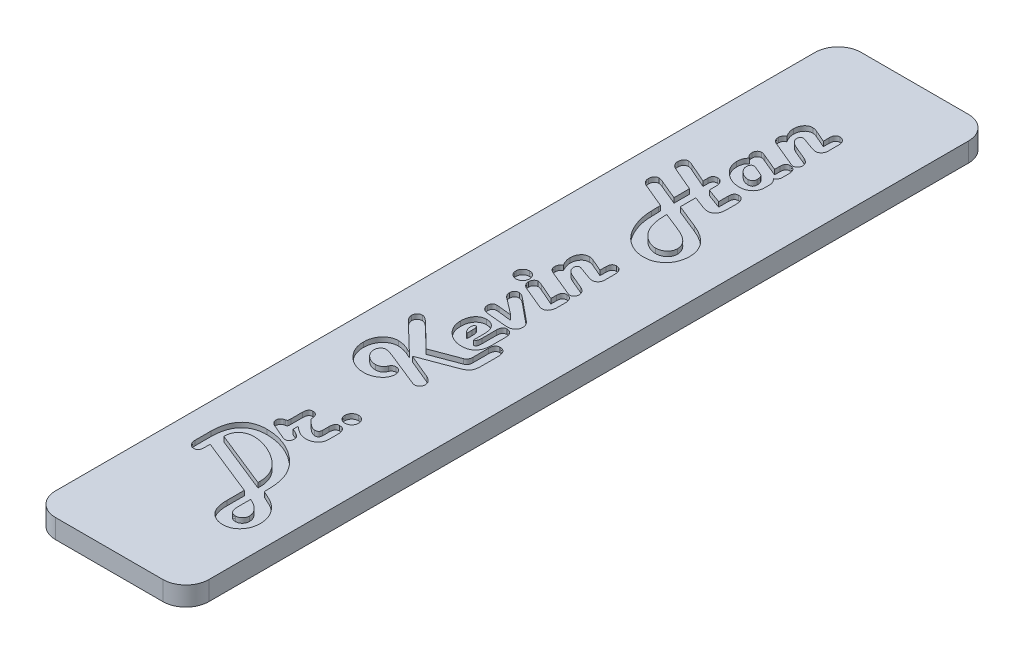
SolidWorks part; units mm, degrees
ref_plane "Front Plane" through (0, 0, 0) normal (0, 0, 1) x (1, 0, 0)
ref_plane "Top Plane" through (0, 0, 0) normal (0, 1, 0) x (1, 0, 0)
ref_plane "Right Plane" through (0, 0, 0) normal (1, 0, 0) x (0, 0, -1)
sketch "Sketch1" plane through (0, 0, 0) normal (0, 0, 1) x (1, 0, 0)
  line L0 (0, 1.5875) -> (0, -1.5875)
  line L1 (-12.7, 0) -> (12.7, 0) construction
  point P6 (0, 0)
  dimension "Width" = 25.4
  dimension "Thk" = 3.175
sketch "Sketch2" plane through (0, 0, 0) normal (1, 0, 0) x (0, 0, -1)
  line L0 (66.675, 0) -> (-66.675, 0)
  point P4 (0, 0)
  dimension "Length" = 133.35
sketch "Sketch3" plane through (0, 0, 0) normal (0, 0, 1) x (1, 0, 0)
  line L1 (12.7, 1.5875) -> (-12.7, 1.5875)
  line L2 (12.7, 1.5875) -> (12.7, -1.5875)
  line L3 (12.7, -1.5875) -> (-12.7, -1.5875)
  line L4 (-12.7, 1.5875) -> (-12.7, -1.5875)
  line L5 (12.7, 1.5875) -> (-12.7, -1.5875) construction
  line L6 (12.7, -1.5875) -> (-12.7, 1.5875) construction
  point P0 (0, 0)
extrude "Boss-Extrude1" add sketch "Sketch3" along normal up to vertex (66.675 mm away) and the other way up to vertex (66.675 mm away) up to point (0, 0, 66.675) other way up to point (0, 0, -66.675)
sketch "Sketch5" plane through (0, 1.5875, 0) normal (0, 1, 0) x (1, 0, 0)
  line L2 (9.652, -66.675) -> (-9.398, -66.675) construction
  line L3 (-12.7, -63.5025) -> (-12.7, 63.627) construction
  line L12 (12.7, -66.675) -> (12.7, 66.675)
  line L13 (12.7, 66.675) -> (-12.7, 66.675)
  line L14 (-12.7, 66.675) -> (-12.7, -66.675)
  line L15 (-12.7, -66.675) -> (12.7, -66.675)
  line L16 (12.7, -62.865) -> (12.7, 62.865)
  line L17 (8.89, 66.675) -> (-8.89, 66.675)
  line L18 (-12.7, 62.865) -> (-12.7, -62.865)
  line L19 (-8.89, -66.675) -> (8.89, -66.675)
  arc A8 (12.7, 62.865) -> (8.89, 66.675) centre (8.89, 62.865) ccw
  arc A9 (-8.89, 66.675) -> (-12.7, 62.865) centre (-8.89, 62.865) ccw
  arc A10 (12.7, -62.865) -> (8.89, -66.675) centre (8.89, -62.865) cw
  arc A11 (-8.89, -66.675) -> (-12.7, -62.865) centre (-8.89, -62.865) cw
  dimension "D2" = 3.81
  dimension "D1" = 0
extrude "Cut-Extrude2" cut sketch "Sketch5" against normal through all flip side to cut
sketch "Sketch4" plane through (0, 1.5875, 0) normal (0, 1, 0) x (1, 0, 0)
  line L0 (0, 0) -> (2.54, 0) construction
  line L1 (2.54, -66.675) -> (2.54, 66.675) construction
  line L2 (8.89, 66.675) -> (-8.89, 66.675) construction
  text T0 "Dr. Kevin Han" font "Harlow Solid Italic" height in points 36
  point P8 (2.54, 0)
  dimension "D1" = 2.54
extrude "Cut-Extrude1" cut sketch "Sketch4" against normal blind 0.7937
